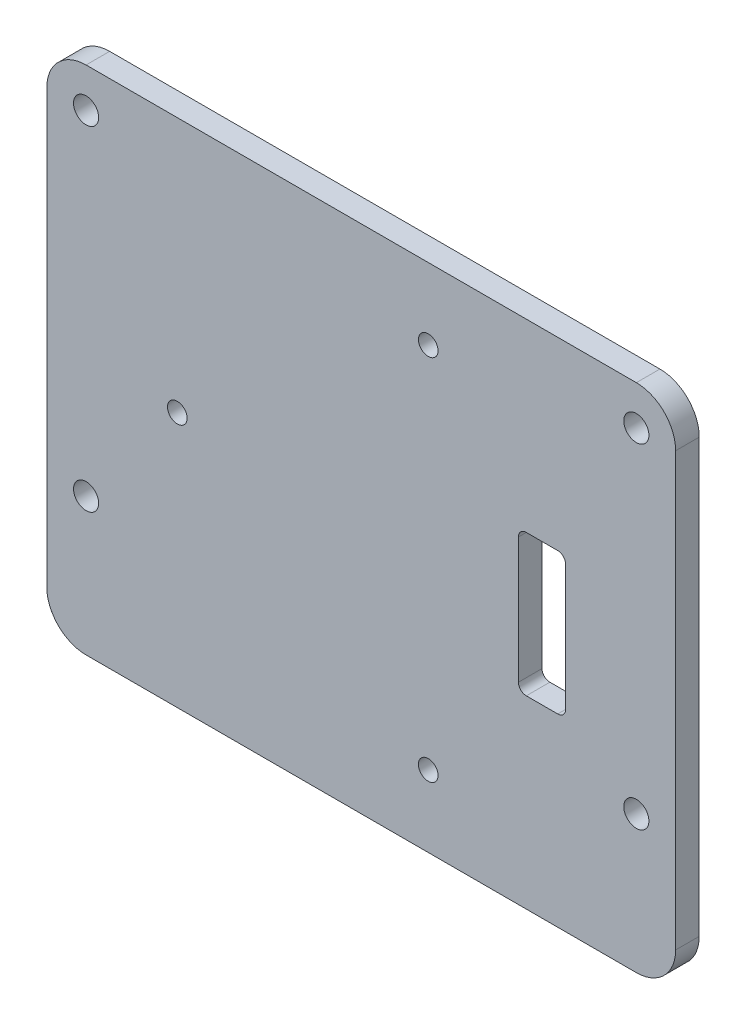
SolidWorks part; units mm, degrees
ref_plane "Front Plane" through (0, 0, 0) normal (0, 0, 1) x (1, 0, 0)
ref_plane "Top Plane" through (0, 0, 0) normal (0, 1, 0) x (1, 0, 0)
ref_plane "Right Plane" through (0, 0, 0) normal (1, 0, 0) x (0, 0, -1)
sketch "Sketch1" plane through (0, 0, 0) normal (0, 0, 1) x (1, 0, 0)
  line L1 (-40, 32.5) -> (40, 32.5)
  line L2 (-40, 32.5) -> (-40, -32.5)
  line L3 (-40, -32.5) -> (40, -32.5)
  line L4 (40, 32.5) -> (40, -32.5)
  circle A0 centre (8.5268, 23.4) radius 1.25 construction
  circle A1 centre (8.5268, -23.4) radius 1.25 construction
  circle A2 centre (-23.3932, 0) radius 1.25 construction
  circle A3 centre (8.5268, 23.4) radius 1.25
  circle A4 centre (8.5268, -23.4) radius 1.25
  circle A5 centre (-23.3932, 0) radius 1.25
  point P4 (0, 32.5)
  point P6 (-40, 0)
  dimension "D1" = 80
  dimension "D2" = 65
extrude "Boss-Extrude1" add sketch "Sketch1" along normal blind 3
fillet "Fillet1" radius 5 4 edges at (40, -32.5, 1.5) (-40, -32.5, 1.5) (40, 32.5, 1.5) (-40, 32.5, 1.5)
sketch "Sketch2" plane through (0, 0, 0) normal (0, 0, -1) x (-1, 0, 0)
  line L0 (-35, 32.5) -> (35, 32.5) construction
  line L1 (-40, -27.5) -> (-40, 27.5) construction
  line L2 (40, 27.5) -> (40, -27.5) construction
  line L3 (-35, 27.5) -> (35, 27.5) construction
  line L4 (-35, 27.5) -> (-35, -15) construction
  line L5 (-35, -15) -> (35, -15) construction
  line L6 (35, 27.5) -> (35, -15) construction
  line L7 (35, -32.5) -> (-35, -32.5) construction
  circle A0 centre (-35, 27.5) radius 1.6
  circle A1 centre (-35, -15) radius 1.6
  circle A2 centre (35, 27.5) radius 1.6
  circle A3 centre (35, -15) radius 1.6
  dimension "D4" = 3.2
  dimension "D1" = 5
  dimension "D2" = 5
  dimension "D3" = 5
  dimension "D5" = 17.5
extrude "Cut-Extrude1" cut sketch "Sketch2" against normal through all
sketch "Sketch4" plane through (0, 0, 0) normal (0, 0, -1) x (-1, 0, 0)
  line L1 (-26, 9) -> (-20, 9)
  line L2 (-26, 9) -> (-26, -9)
  line L3 (-26, -9) -> (-20, -9)
  line L4 (-20, 9) -> (-20, -9)
  point P4 (-20, 0)
  dimension "D2" = 18
  dimension "D1" = 6
  dimension "D3" = 20
extrude "Cut-Extrude2" cut sketch "Sketch4" against normal through all
fillet "Fillet2" radius 1 4 edges at (26, -9, 1.5) (26, 9, 1.5) (20, -9, 1.5) (20, 9, 1.5)
